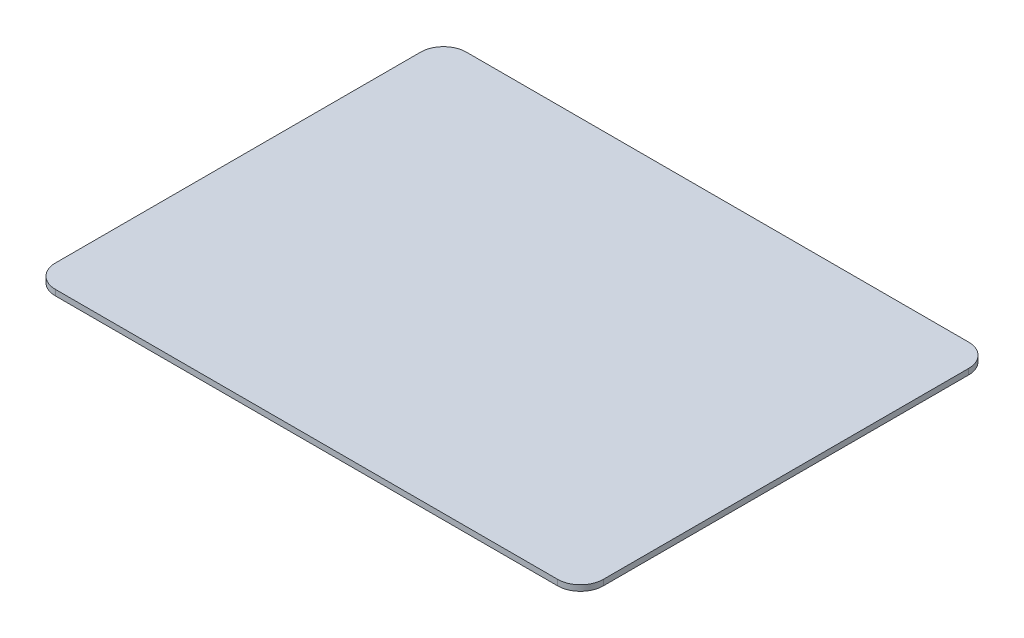
SolidWorks part; units mm, degrees
ref_plane "Front Plane" through (0, 0, 0) normal (0, 0, 1) x (1, 0, 0)
ref_plane "Top Plane" through (0, 0, 0) normal (0, 1, 0) x (1, 0, 0)
ref_plane "Right Plane" through (0, 0, 0) normal (1, 0, 0) x (0, 0, -1)
sketch "Sketch1" plane through (0, 0, 0) normal (0, 1, 0) x (1, 0, 0)
  line L1 (-139.7, -114.3) -> (139.7, -114.3)
  line L2 (-152.4, -101.6) -> (-152.4, 101.6)
  line L3 (-139.7, 114.3) -> (139.7, 114.3)
  line L4 (152.4, -101.6) -> (152.4, 101.6)
  line L5 (-152.4, -114.3) -> (152.4, 114.3) construction
  line L6 (-152.4, 114.3) -> (152.4, -114.3) construction
  arc A0 (152.4, 101.6) -> (139.7, 114.3) centre (139.7, 101.6) ccw
  arc A1 (139.7, -114.3) -> (152.4, -101.6) centre (139.7, -101.6) ccw
  arc A2 (-152.4, -101.6) -> (-139.7, -114.3) centre (-139.7, -101.6) ccw
  arc A3 (-152.4, 101.6) -> (-139.7, 114.3) centre (-139.7, 101.6) cw
  point P0 (0, 0)
  dimension "D3" = 12.7
  dimension "D1" = 304.8
  dimension "D2" = 228.6
extrude "Boss-Extrude1" add sketch "Sketch1" along normal blind 3.175
